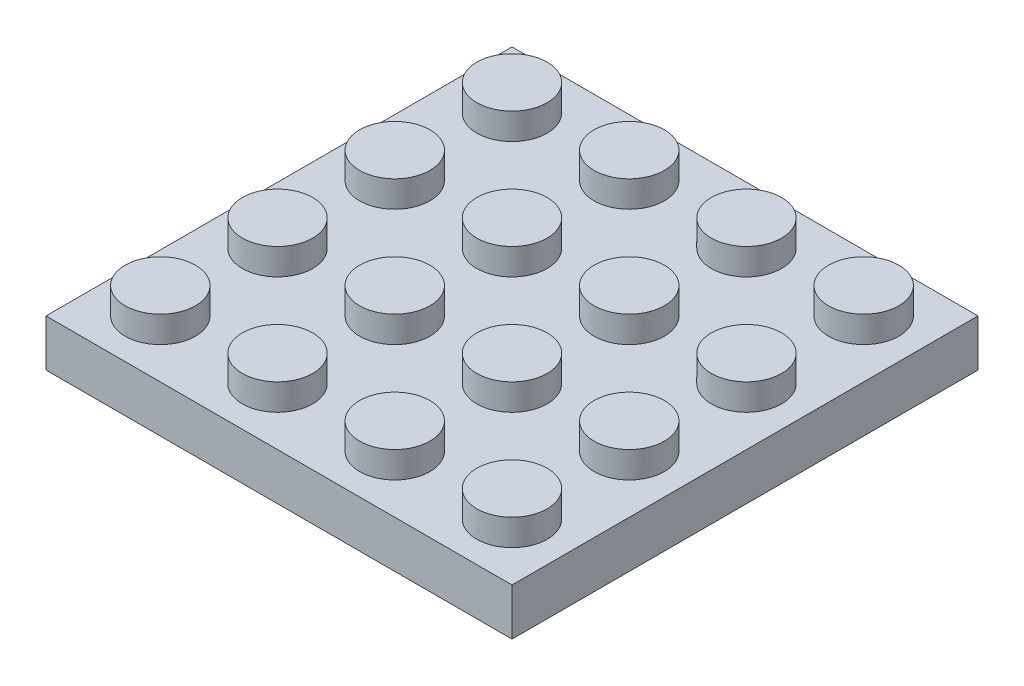
SolidWorks part; units mm, degrees
ref_plane "Front Plane" through (0, 0, 0) normal (0, 0, 1) x (1, 0, 0)
ref_plane "Top Plane" through (0, 0, 0) normal (0, 1, 0) x (1, 0, 0)
ref_plane "Right Plane" through (0, 0, 0) normal (1, 0, 0) x (0, 0, -1)
sketch "Sketch1" plane through (0, 0, 0) normal (0, 1, 0) x (1, 0, 0)
  line L1 (-15.9, -15.9) -> (15.9, -15.9)
  line L2 (-15.9, -15.9) -> (-15.9, 15.9)
  line L3 (-15.9, 15.9) -> (15.9, 15.9)
  line L4 (15.9, -15.9) -> (15.9, 15.9)
  line L5 (-15.9, -15.9) -> (15.9, 15.9) construction
  line L6 (-15.9, 15.9) -> (15.9, -15.9) construction
  point P0 (0, 0)
  dimension "D1" = 31.8
extrude "Boss-Extrude1" add sketch "Sketch1" along normal blind 3.2
sketch "Sketch2" plane through (0, 3.2, 0) normal (0, 1, 0) x (1, 0, 0)
  line L0 (-15.9, -15.9) -> (15.9, -15.9) construction
  line L1 (-15.9, 15.9) -> (-15.9, -15.9) construction
  circle A0 centre (-12, -12) radius 2.4
  dimension "D1" = 4.8
  dimension "D2" = 3.9
  dimension "D3" = 3.9
extrude "Boss-Extrude2" add sketch "Sketch2" along normal blind 1.8
pattern_linear "LPattern1" count 4 spacing 8 along (1, 0, 0) count 4 spacing 8 along (0, 0, -1) of "Boss-Extrude2"
shell "Shell1" thickness 1.2
sketch "Sketch3" plane through (0, 2, 0) normal (0, -1, 0) x (1, 0, 0)
  line L0 (-12, 12) -> (-4, 4) construction
  line L1 (-12, 4) -> (-4, 12) construction
  circle A0 centre (-8, 8) radius 3.25
  circle A1 centre (-8, 8) radius 2.4
  dimension "D1" = 6.5
  dimension "D2" = 4.8
extrude "Boss-Extrude3" add sketch "Sketch3" along normal up to surface (2 mm away) up to face at (0, 0, 0)
pattern_linear "LPattern2" count 3 spacing 8 along (1, 0, 0) count 3 spacing 8 along (0, 0, -1) of "Boss-Extrude3"
